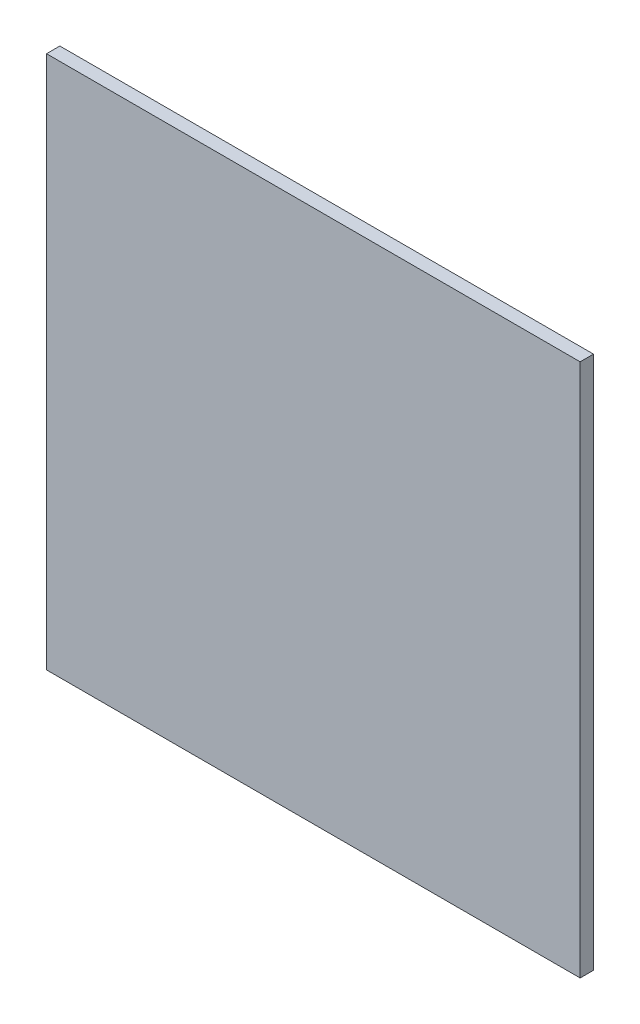
SolidWorks part; units mm, degrees
ref_plane "Front" through (0, 0, 0) normal (0, 0, 1) x (1, 0, 0)
ref_plane "Top" through (0, 0, 0) normal (0, 1, 0) x (1, 0, 0)
ref_plane "Right" through (0, 0, 0) normal (1, 0, 0) x (0, 0, -1)
sketch "草图3" plane through (0, 0, 0) normal (0, 0, 1) x (1, 0, 0)
  line L1 (0, 0) -> (4000, 0)
  line L2 (0, 0) -> (0, 4000)
  line L3 (0, 4000) -> (4000, 4000)
  line L4 (4000, 0) -> (4000, 4000)
  dimension "D1" = 4000
  dimension "D2" = 4000
extrude "凸台-拉伸2" add sketch "草图3" against normal blind 100
sketch "草图6" plane through (0, 0, -100) normal (0, 0, -1) x (-1, 0, 0)
  line L0 (-4000, 0) -> (-4000, 4000) construction
  line L1 (0, 0) -> (-4000, 0) construction
  spline S0 degree 3 poles (-250, 200) (-510.3786, 206.0173) (-896.848, 183.4384) (-1584.8963, 40.3923) (-1989.2863, 36.8058) (-2510.5564, 257.5477) (-2608.3951, 789.5193) (-2883.3861, 1115.1138) (-3427.472, 494.924) (-3819.2804, 718.3207) (-3735.2202, 1499.199) (-3594.311, 2076.8465) (-3328.2343, 3113.2655) (-2868.4154, 4019.6192) (-1900, 3800) knots 0 0 0 0 0.128 0.153886 0.247193 0.270422 0.362953 0.385789 0.47595 0.499541 0.610434 0.666951 0.736845 1 1 1 1
  point P0 (-250, 200)
  point P1 (-1300, 100)
  point P2 (-2250, 150)
  point P3 (-2750, 950)
  point P4 (-3600, 600)
  point P5 (-3700, 1600)
  point P6 (-3600, 2050)
  point P7 (-3450, 2600)
  point P8 (-3000, 3500)
  point P9 (-1900, 3800)
  dimension "D1" = 3750
  dimension "D2" = 200
  dimension "D3" = 100
  dimension "D4" = 2700
  dimension "D5" = 150
  dimension "D6" = 1750
  dimension "D7" = 1250
  dimension "D8" = 950
  dimension "D9" = 400
  dimension "D10" = 600
  dimension "D11" = 300
  dimension "D12" = 1600
  dimension "D13" = 400
  dimension "D14" = 2050
  dimension "D15" = 550
  dimension "D16" = 2600
  dimension "D17" = 1000
  dimension "D18" = 3500
  dimension "D19" = 3800
  dimension "D20" = 2100
